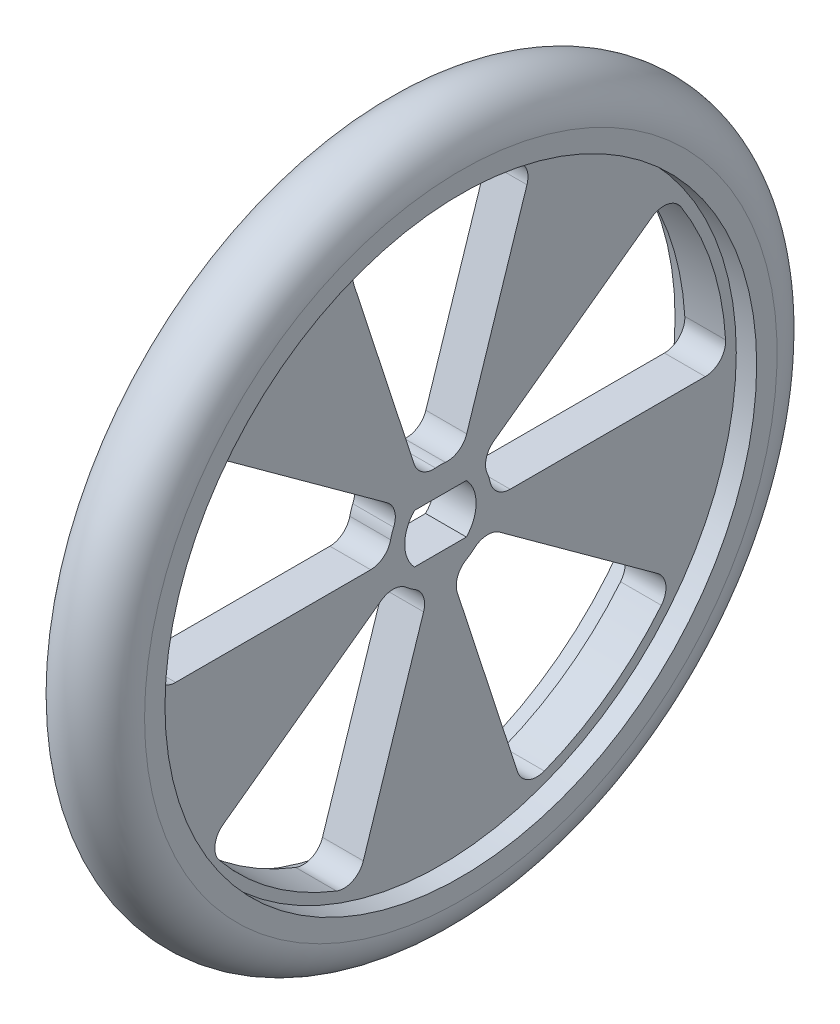
SolidWorks part; units mm, degrees
ref_plane "Front Plane" through (0, 0, 0) normal (0, 0, 1) x (1, 0, 0)
ref_plane "Top Plane" through (0, 0, 0) normal (0, 1, 0) x (1, 0, 0)
ref_plane "Right Plane" through (0, 0, 0) normal (1, 0, 0) x (0, 0, -1)
ref_axis "Axis1" through (-0.381, 0, 0) along (1, 0, 0)
sketch "Sketch1" plane through (0, 0, 0) normal (1, 0, 0) x (0, 0, -1)
  circle A0 centre (0, 0) radius 31
  dimension "D1" = 62
extrude "Boss-Extrude1" add sketch "Sketch1" along normal blind 8
ref_plane "Plane1" through (4, 0, 0) normal (1, 0, 0) x (0, 0, -1)
sketch "Sketch3" plane through (8, 0, 0) normal (1, 0, 0) x (0, 0, -1)
  circle A0 centre (0, 0) radius 29
  circle A2 centre (0, 0) radius 31 construction
  dimension "D1" = 2
extrude "Cut-Extrude1" cut sketch "Sketch3" against normal blind 2
sketch "Sketch4" plane through (6, 0, 0) normal (1, 0, 0) x (0, 0, -1)
  line L0 (0, 0) -> (0, 50000) construction
  line L1 (-2, 4.5826) -> (49998, 4.5826) construction
  line L2 (-2, 4.5826) -> (-9.1134, 26.4754)
  line L3 (2, 4.5826) -> (9.1134, 26.4754)
  arc A0 (-2, 4.5826) -> (2, 4.5826) centre (0, 0) cw
  arc A1 (-9.1134, 26.4754) -> (9.1134, 26.4754) centre (0, 0) cw
  circle A2 centre (0, 0) radius 29 construction
  dimension "D2" = 5
  dimension "D3" = 1
  dimension "D1" = 36
  dimension "D4" = 4
extrude "Cut-Extrude2" cut sketch "Sketch4" against normal through all
fillet "Fillet2" radius 2 4 edges at (3, 4.5826, -2) (3, 4.5826, 2) (3, 26.4754, 9.1134) (3, 26.4754, -9.1134)
pattern_circular "CirPattern1" count 5 over 360 about axis through (0, 0, 0) along (1, 0, 0) of "Cut-Extrude2", "Fillet2"
mirror "Mirror1" about plane through (4, 0, 0) normal (1, 0, 0) of "Cut-Extrude1"
sketch "Sketch5" plane through (6, 0, 0) normal (1, 0, 0) x (0, 0, -1)
  line L0 (-2.5475, 2.4) -> (2.5475, 2.4)
  line L1 (0, 0) -> (50000, 0) construction
  line L2 (-2.5475, -2.4) -> (2.5475, -2.4)
  circle A0 centre (0, 0) radius 3.5 construction
  arc A1 (-2.5475, 2.4) -> (-2.5475, -2.4) centre (0, 0) ccw
  arc A2 (2.5475, 2.4) -> (2.5475, -2.4) centre (0, 0) cw
  dimension "D1" = 7
  dimension "D2" = 4.8
extrude "Cut-Extrude3" cut sketch "Sketch5" against normal up to next
sketch "Sketch6" plane through (0, 0, 0) normal (0, 0, 1) x (1, 0, 0)
  line L0 (0, 31) -> (8, 31)
  arc A0 (0, 31) -> (8, 31) centre (4, 31) cw
revolve "Revolve1" add sketch "Sketch6" angle 360 about axis through (-0.381, 0, 0) along (1, 0, 0)
ref_plane "Plane2" through (0, -35, 0) normal (0, 1, 0) x (1, 0, 0)
